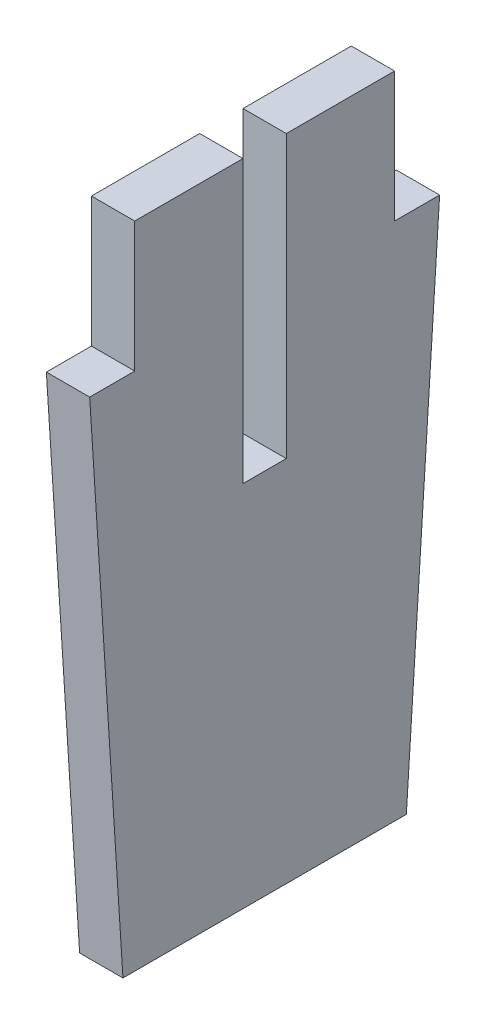
SolidWorks part; units mm, degrees
ref_plane "Front Plane" through (0, 0, 0) normal (0, 0, 1) x (1, 0, 0)
ref_plane "Top Plane" through (0, 0, 0) normal (0, 1, 0) x (1, 0, 0)
ref_plane "Right Plane" through (0, 0, 0) normal (1, 0, 0) x (0, 0, -1)
sketch "Sketch1" plane through (0, 0, 0) normal (1, 0, 0) x (0, 0, -1)
  line L0 (0, 55) -> (0, -55) construction
  line L1 (0, 47.625) -> (7.9375, 47.625)
  line L2 (0, 47.625) -> (0, 38.1)
  line L3 (-3.302, 38.1) -> (22.352, 38.1) construction
  line L4 (19.05, 47.625) -> (19.05, 38.1)
  line L5 (0, 38.1) -> (-3.302, 38.1)
  line L6 (9.525, 38.1) -> (9.525, 6.35) construction
  line L7 (19.05, 38.1) -> (22.352, 38.1)
  line L8 (-1.27, 6.35) -> (20.32, 6.35) construction
  line L9 (-3.302, 38.1) -> (-1.27, 6.35)
  line L10 (22.352, 38.1) -> (20.32, 6.35)
  line L11 (20.32, 6.35) -> (19.9136, 0)
  line L12 (-1.27, 6.35) -> (-0.8636, 0)
  line L13 (-0.8636, 0) -> (19.9136, 0)
  line L14 (55, 0) -> (-55, 0) construction
  line L15 (11.1125, 47.625) -> (19.05, 47.625)
  line L16 (0, 47.625) -> (11.1125, 47.625) construction
  line L17 (11.1125, 47.625) -> (11.1125, 26.9875)
  line L18 (11.1125, 26.9875) -> (7.9375, 26.9875)
  line L19 (7.9375, 47.625) -> (7.9375, 26.9875)
  line L20 (11.1125, 47.625) -> (7.9375, 26.9875) construction
  line L21 (11.1125, 26.9875) -> (7.9375, 47.625) construction
  line L27 (11.1125, 47.625) -> (19.05, 47.625) construction
  point P8 (9.525, 37.3063)
  dimension "D1" = 9.525
  dimension "D2" = 19.05
  dimension "D3" = 25.654
  dimension "D4" = 31.75
  dimension "D5" = 21.59
  dimension "D6" = 6.35
  dimension "D7" = 20.7772
  dimension "D8" = 20.7772
  dimension "D9" = 3.175
  dimension "D10" = 20.6375
extrude "Boss-Extrude1" add sketch "Sketch1" along normal blind 3.175
